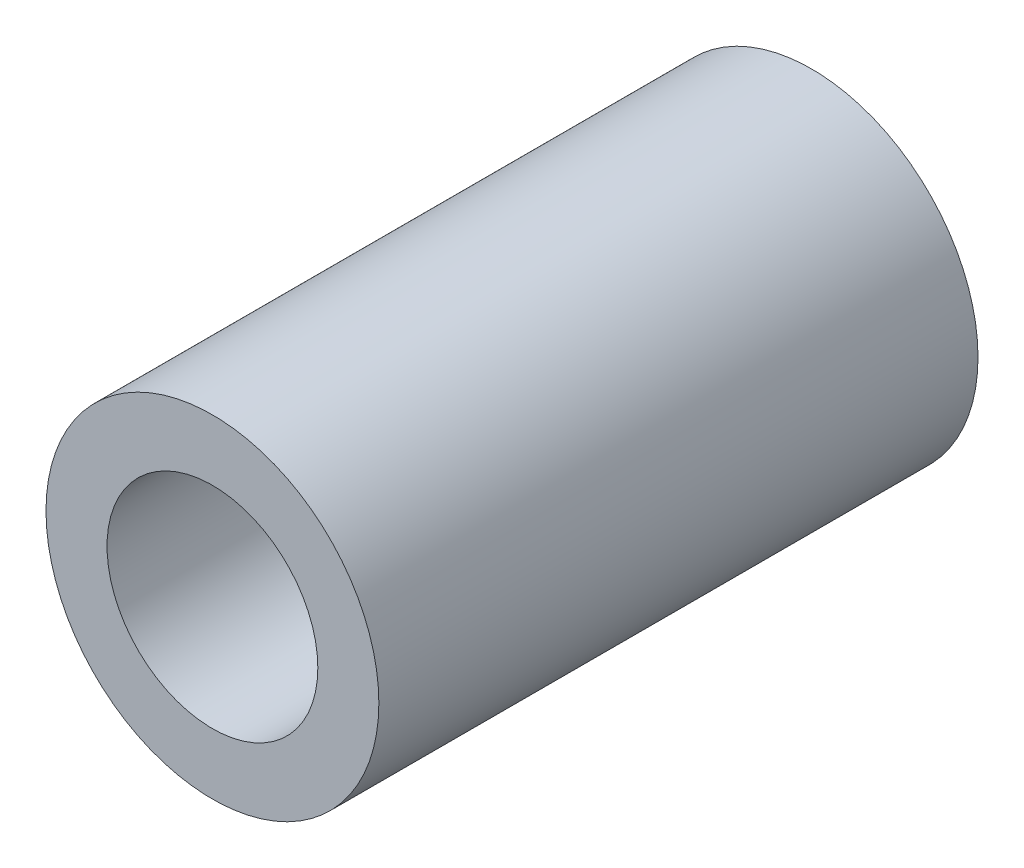
SolidWorks part; units mm, degrees
ref_plane "Plan de face" through (0, 0, 0) normal (0, 0, 1) x (1, 0, 0)
ref_plane "Plan de dessus" through (0, 0, 0) normal (0, 1, 0) x (1, 0, 0)
ref_plane "Plan de droite" through (0, 0, 0) normal (1, 0, 0) x (0, 0, -1)
sketch "Esquisse1" plane through (0, 0, 0) normal (0, 0, 1) x (1, 0, 0)
  circle A0 centre (0, 0) radius 4.75
  circle A1 centre (0, 0) radius 7.5
  dimension "D1" = 9.5
  dimension "D2" = 15
extrude "Boss.-Extru.1" add sketch "Esquisse1" along normal blind 27
